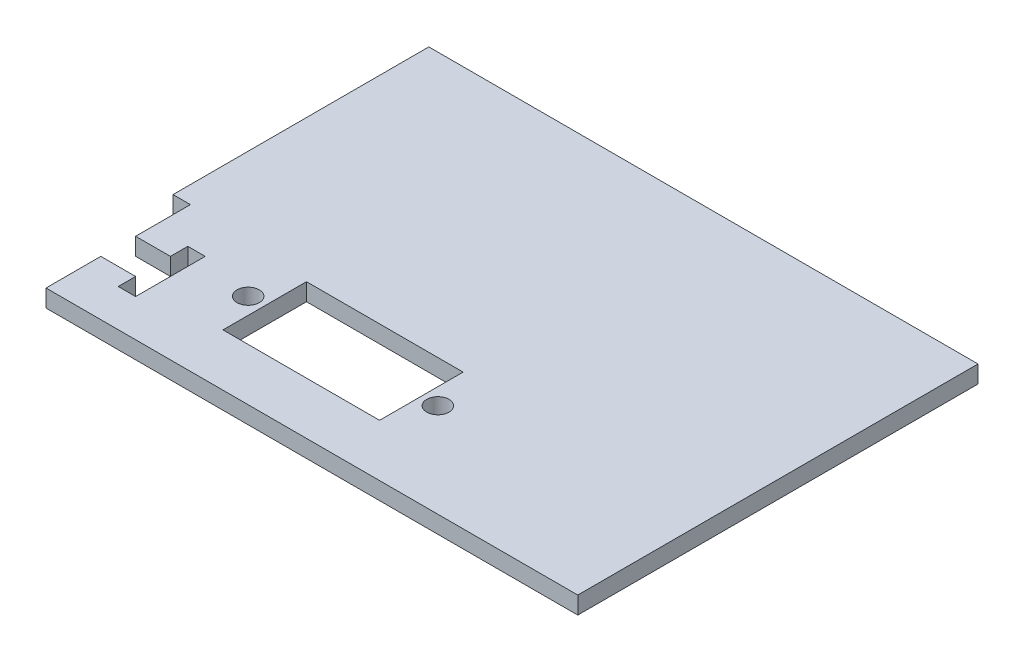
SolidWorks part; units mm, degrees
ref_plane "Front Plane" through (0, 0, 0) normal (0, 0, 1) x (1, 0, 0)
ref_plane "Top Plane" through (0, 0, 0) normal (0, 1, 0) x (1, 0, 0)
ref_plane "Right Plane" through (0, 0, 0) normal (1, 0, 0) x (0, 0, -1)
sketch "Sketch1" plane through (0, 0, 0) normal (0, 1, 0) x (1, 0, 0)
  line L1 (40, -30) -> (-40, -30)
  line L2 (40, -30) -> (40, 30)
  line L3 (40, 30) -> (-40, 30)
  line L4 (-40, -30) -> (-40, 30)
  line L5 (40, -30) -> (-40, 30) construction
  line L6 (40, 30) -> (-40, -30) construction
  point P0 (0, 0)
  dimension "D1" = 80
  dimension "D2" = 60
extrude "Boss-Extrude1" add sketch "Sketch1" along normal blind 2.5 contours L2 L1 L4 L3
sketch "Sketch2" plane through (0, 0, 0) normal (0, 1, 0) x (1, 0, 0)
  line L0 (0, -30) -> (0, -24)
  line L1 (40, -30) -> (-40, -30) construction
  line L2 (-11, -24) -> (21, -24)
  line L3 (-8.625, -24) -> (0, -24)
  line L4 (-11, -24) -> (-6.25, -24)
  line L5 (21, -24) -> (16.25, -24)
  line L6 (16.25, -30) -> (-6.25, -30)
  line L7 (16.25, -30) -> (16.25, -18)
  line L8 (16.25, -18) -> (-6.25, -18)
  line L9 (-6.25, -30) -> (-6.25, -18)
  line L10 (16.25, -30) -> (-6.25, -18) construction
  line L11 (16.25, -18) -> (-6.25, -30) construction
  line L12 (-10.225, -24) -> (0, -24)
  line L13 (-8.625, -24) -> (0, -24)
  circle A2 centre (0, -24) radius 2.5
  circle A3 centre (-8.625, -24) radius 1.6
  circle A4 centre (18.625, -24) radius 1.6
  point P5 (0, -30)
  point P15 (5, -24)
  dimension "D5" = 3.2
  dimension "D7" = 3.2
  dimension "D8" = 5
  dimension "D1" = 6
  dimension "D2" = 11
  dimension "D3" = 32
  dimension "D4" = 4.75
  dimension "D6" = 4.75
  dimension "D9" = 12
  dimension "D10" = 22.5
extrude "Cut-Extrude4" cut sketch "Sketch2" against normal through all and the other way through all contours A2 L2 L7 L8 L9 | A2 L0 L6 L7 L2 | L0 A2 L2 | L2 A2 | L2 A2 L0 | A2 L2 L9 L6 L0 | A3 | A4
sketch "Sketch3" plane through (0, 2.5, 0) normal (0, 1, 0) x (1, 0, 0)
  line L0 (-10.225, -24) -> (0.275, -24)
  line L3 (-40, -30) -> (-37.5, -30)
  line L4 (-40, -30) -> (-40, -9.5)
  line L5 (-40, -9.5) -> (-37.5, -9.5)
  line L6 (-37.5, -30) -> (-37.5, -9.5)
  circle A0 centre (-8.625, -24) radius 1.6 construction
  line M13 (-40, 30) -> (-40, -30)
  line M14 (-40, -30) -> (-6.25, -30)
  dimension "D1" = 10.5
  dimension "D2" = 2.5
  dimension "D3" = 20.5
extrude "Boss-Extrude2" add sketch "Sketch3" along normal blind 66.5 contours L6 L5 M14 M13
sketch "Sketch4" plane through (0, 2.5, 0) normal (0, 1, 0) x (1, 0, 0)
  line L1 (40, -30) -> (-40, -30)
  line L2 (40, -30) -> (40, -35.5)
  line L3 (40, -35.5) -> (-40, -35.5)
  line L4 (-40, -30) -> (-40, -35.5)
  dimension "D1" = 5.5
extrude "Boss-Extrude3" add sketch "Sketch4" against normal up to surface (2.5 mm away) up to face at (18.625, 0, 22.4)
sketch "Sketch5" plane through (0, 2.5, 0) normal (0, 1, 0) x (1, 0, 0)
  line L1 (-37.5, -30) -> (-40, -30)
  line L2 (-37.5, -30) -> (-37.5, -35.5)
  line L3 (-37.5, -35.5) -> (-40, -35.5)
  line L4 (-40, -30) -> (-40, -35.5)
extrude "Boss-Extrude4" add sketch "Sketch5" along normal up to surface (66.5 mm away) up to face at (-38.75, 69, 19.75)
sketch "Sketch6" plane through (0, 69, 0) normal (0, 1, 0) x (1, 0, 0)
  line L0 (-37.5, -35.5) -> (-37.5, -9.5) construction
  line L1 (-40, -9.5) -> (-37.5, -9.5)
  line L2 (-40, -9.5) -> (-40, -15)
  line L3 (-40, -15) -> (-37.5, -15)
  line L4 (-37.5, -9.5) -> (-37.5, -15)
  dimension "D1" = 5.5
extrude "Cut-Extrude5" cut sketch "Sketch6" against normal up to surface (66.5 mm away) up to face at (5, 2.5, 24)
sketch "Sketch7" plane through (0, 2.5, 0) normal (0, 1, 0) x (1, 0, 0)
  line L0 (-10.225, -24) -> (0.275, -24)
  line L1 (15.525, -24) -> (-14.975, -24)
  line L2 (15.525, -24) -> (18.625, -24)
  line L3 (-14.975, -24) -> (-24.175, -24)
  circle A0 centre (-8.625, -24) radius 1.6 construction
  point P8 (0.275, -24)
  dimension "D4" = 9.2
  dimension "D1" = 10.5
  dimension "D2" = 30.5
  dimension "D3" = 3.1
sketch "Sketch9" plane through (0, 2.5, 0) normal (0, 1, 0) x (1, 0, 0)
  line L0 (-10.225, -24) -> (-37.5, -24)
  line L1 (-37.5, -35.5) -> (-37.5, -15) construction
  line L2 (-37.5, -24) -> (-37.5, -35.5)
  line L3 (-37.5, -24) -> (-37.5, -12.5)
  line L4 (-37.5, -12.5) -> (-40, -12.5)
  line L5 (-40, -15) -> (-40, 30) construction
  line L6 (-40, -12.5) -> (-40, -15)
  line L7 (-40, -15) -> (-37.5, -15) construction
  line L8 (-40, -15) -> (-37.5, -15)
  line L9 (-37.5, -15) -> (-37.5, -12.5)
  dimension "D1" = 11.5
extrude "Boss-Extrude5" add sketch "Sketch9" along normal up to surface (66.5 mm away) contours L4 L6 L8 L9 up to face at (-38.75, 69, 25.25)
sketch "Sketch11" plane through (-37.5, 0, 0) normal (1, 0, 0) x (0, 0, -1)
  line L0 (-24, 69) -> (-24, 54)
  line L1 (-35.5, 69) -> (-12.5, 69) construction
  circle A0 centre (-24, 54) radius 4.75
  dimension "D2" = 9.5
  dimension "D1" = 15
extrude "Cut-Extrude6" cut sketch "Sketch11" against normal up to surface (2.5 mm away) contours A0 up to face at (-40, 23.8333, 6)
sketch "Sketch13" plane through (-40, 0, 0) normal (-1, 0, 0) x (0, 0, 1)
  line L0 (24, 54) -> (32, 54)
  line L1 (32, 36.5) -> (32, 71.5)
  point P7 (32, 54)
  dimension "D1" = 8
  dimension "D2" = 35
sketch "Sketch15" plane through (0, 69, 0) normal (0, 1, 0) x (1, 0, 0)
  line L1 (-40, -12.5) -> (-37.5, -12.5)
  line L2 (-40, -12.5) -> (-40, -35.5)
  line L3 (-40, -35.5) -> (-37.5, -35.5)
  line L4 (-37.5, -12.5) -> (-37.5, -35.5)
extrude "Boss-Extrude6" add sketch "Sketch15" along normal blind 8
sketch "Sketch17" plane through (0, 0, 35.5) normal (0, 0, 1) x (1, 0, 0)
  line L1 (-40, 77) -> (-37.5, 77)
  line L2 (-40, 77) -> (-40, 2.5)
  line L3 (-40, 2.5) -> (-37.5, 2.5)
  line L4 (-37.5, 77) -> (-37.5, 2.5)
extrude "Boss-Extrude7" add sketch "Sketch17" along normal blind 2
sketch "Sketch18" plane through (-40, 0, 0) normal (-1, 0, 0) x (0, 0, 1)
  circle A0 centre (32, 36.5) radius 1.6
  circle A1 centre (32, 71.5) radius 1.6
  dimension "D1" = 3.2
  dimension "D2" = 3.2
extrude "Cut-Extrude7" cut sketch "Sketch18" against normal up to surface (2.5 mm away) up to face at (-37.5, 54, 19.25)
sketch "Sketch21" plane through (0, 0, 35.5) normal (0, 0, 1) x (1, 0, 0)
  line L1 (-40, 2.5) -> (40, 2.5)
  line L2 (-40, 2.5) -> (-40, 0)
  line L3 (-40, 0) -> (40, 0)
  line L4 (40, 2.5) -> (40, 0)
extrude "Boss-Extrude8" add sketch "Sketch21" along normal up to surface (2 mm away) up to face at (-38.75, 39.75, 37.5)
sketch "Sketch22" plane through (-37.5, 0, 0) normal (1, 0, 0) x (0, 0, -1)
  line L0 (-37.5, 2.5) -> (-12.5, 2.5) construction
  line L1 (-12.5, 77) -> (-16.75, 77)
  line L2 (-12.5, 77) -> (-12.5, 2.5)
  line L3 (-12.5, 2.5) -> (-16.75, 2.5)
  line L4 (-16.75, 77) -> (-16.75, 2.5)
  dimension "D1" = 4.25
extrude "Cut-Extrude8" cut sketch "Sketch22" against normal up to surface (2.5 mm away) up to face at (-40, 36.5, 33.6)
fillet "Fillet1" radius 5 2 edges at (-38.75, 77, 37.5) (-38.75, 77, 16.75)
sketch "Sketch23" plane through (0, 2.5, 0) normal (0, 1, 0) x (1, 0, 0)
  line L0 (20.225, -24) -> (55.225, -24)
  line L1 (40, 30) -> (40, -37.5)
  line L6 (40, -37.5) -> (55.225, -37.5)
  line L7 (55.225, -37.5) -> (55.225, 30)
  line L8 (55.225, 30) -> (40, 30)
  circle A0 centre (18.625, -24) radius 1.6 construction
  dimension "D1" = 35
extrude "Boss-Extrude10" add sketch "Sketch23" against normal up to surface (2.5 mm away) contours L8 L1 L6 L7 up to face at (0, 0, 3.75)
sketch "Sketch24" plane through (0, 2.5, 0) normal (0, 1, 0) x (1, 0, 0)
  line L0 (55.225, -37.5) -> (55.225, 30) construction
  line L1 (-40, 30) -> (55.225, 30)
  line L2 (-40, 30) -> (-40, 20)
  line L3 (-40, 20) -> (55.225, 20)
  line L4 (55.225, 30) -> (55.225, 20)
  dimension "D1" = 10
extrude "Cut-Extrude9" cut sketch "Sketch24" against normal through all
sketch "Sketch26" plane through (0, 2.5, 0) normal (0, 1, 0) x (1, 0, 0)
  line L0 (-24.175, -37.5) -> (-24.175, -16.75)
  line L1 (55.225, -37.5) -> (-37.5, -37.5) construction
  line L2 (-24.175, -16.75) -> (-26.675, -16.75)
  line L3 (-26.675, -16.75) -> (-26.675, -37.5)
  line L4 (-26.675, -37.5) -> (-24.175, -37.5)
extrude "Boss-Extrude11" add sketch "Sketch26" along normal up to surface (74.5 mm away) up to face at (-38.75, 77, 27.125)
sketch "Sketch27" plane through (-24.175, 0, 0) normal (1, 0, 0) x (0, 0, -1)
  line L0 (-24, 2.5) -> (-24, 36.275)
  line L2 (-24, 36.275) -> (-32, 36.275)
  line L4 (-32, 18.775) -> (-32, 53.775)
  circle A0 centre (-24, 36.275) radius 4.75
  circle A1 centre (-32, 53.775) radius 1.6
  circle A2 centre (-32, 18.775) radius 1.6
  point P4 (-32, 36.275)
  dimension "D2" = 9.5
  dimension "D5" = 3.2
  dimension "D6" = 3.2
  dimension "D1" = 33.775
  dimension "D3" = 8
  dimension "D4" = 35
extrude "Cut-Extrude10" cut sketch "Sketch27" against normal up to surface (2.5 mm away) contours L0 A0 L2 | L2 A0 L0 | A2 | A1 up to face at (-26.675, 39.75, 27.125)
sketch "Sketch28" plane through (0, 77, 0) normal (0, 1, 0) x (1, 0, 0)
  line L1 (-40, -16.75) -> (-37.5, -16.75)
  line L2 (-40, -16.75) -> (-40, -37.5)
  line L3 (-40, -37.5) -> (-37.5, -37.5)
  line L4 (-37.5, -16.75) -> (-37.5, -37.5)
extrude "Cut-Extrude11" cut sketch "Sketch28" against normal up to surface (74.5 mm away) up to face at (5, 2.5, 24)
sketch "Sketch29" plane through (-24.175, 0, 0) normal (1, 0, 0) x (0, 0, -1)
  line L0 (-32, 55.375) -> (-32, 57.375)
  line L1 (-32, 36.5) -> (-32, 71.5) construction
  line L2 (-16.75, 77) -> (-16.75, 2.5) construction
  line L3 (-37.5, 77) -> (-16.75, 77)
  line L4 (-37.5, 77) -> (-37.5, 57.375)
  line L5 (-37.5, 57.375) -> (-16.75, 57.375)
  line L6 (-16.75, 77) -> (-16.75, 57.375)
  circle A0 centre (-32, 53.775) radius 1.6 construction
  dimension "D1" = 2
extrude "Cut-Extrude12" cut sketch "Sketch29" against normal up to surface (2.5 mm away) contours L4 L3 L6 L5 up to face at (-26.675, 36.275, 19.25)
fillet "Fillet2" radius 6 2 edges at (-25.425, 57.375, 16.75) (-25.425, 57.375, 37.5)
sketch "Sketch31" plane through (0, 2.5, 0) normal (0, 1, 0) x (1, 0, 0)
  line L1 (-40, 20) -> (-26.675, 20)
  line L2 (-40, 20) -> (-40, -37.5)
  line L3 (-40, -37.5) -> (-26.675, -37.5)
  line L4 (-26.675, 20) -> (-26.675, -37.5)
extrude "Cut-Extrude13" cut sketch "Sketch31" against normal up to surface (2.5 mm away) up to face at (7.6125, 0, 8.75)
sketch "Sketch33" plane through (0, 2.5, 0) normal (0, 1, 0) x (1, 0, 0)
  line L0 (55.225, -37.5) -> (-24.175, -37.5) construction
  line L1 (55.225, 20) -> (52.225, 20)
  line L2 (55.225, 20) -> (55.225, -37.5)
  line L3 (55.225, -37.5) -> (52.225, -37.5)
  line L4 (52.225, 20) -> (52.225, -37.5)
  dimension "D1" = 3
extrude "Cut-Extrude14" cut sketch "Sketch33" against normal up to surface (2.5 mm away) up to face at (14.275, 0, 8.75)
sketch "Sketch34" plane through (0, 2.5, 0) normal (0, 1, 0) x (1, 0, 0)
  line L0 (-24.175, -27.125) -> (-24.175, -24.625)
  line L1 (-24.175, -37.5) -> (-24.175, -16.75) construction
  line L2 (-24.175, -27.125) -> (-24.175, -29.625)
  line L3 (-16.675, -32.125) -> (-16.675, -22.125)
  line L4 (-19.175, -24.625) -> (-19.175, -22.125)
  line L5 (-24.175, -29.625) -> (-19.175, -29.625)
  line L6 (-24.175, -29.625) -> (-24.175, -24.625)
  line L7 (-24.175, -24.625) -> (-19.175, -24.625)
  line L8 (-19.175, -29.625) -> (-19.175, -24.625)
  line L9 (-19.175, -29.625) -> (-19.175, -32.125)
  line L10 (-19.175, -32.125) -> (-16.675, -32.125)
  line L11 (-16.675, -22.125) -> (-19.175, -22.125)
  dimension "D1" = 2.5
  dimension "D2" = 2.5
  dimension "D3" = 5
  dimension "D4" = 2.5
  dimension "D5" = 2.5
  dimension "D6" = 2.5
extrude "Cut-Extrude15" cut sketch "Sketch34" against normal up to surface (2.5 mm away)
sketch "Sketch35" plane through (0, 57.375, 0) normal (0, 1, 0) x (1, 0, 0)
  line L1 (-24.175, -16.75) -> (-26.675, -16.75)
  line L2 (-24.175, -16.75) -> (-24.175, -37.5)
  line L3 (-24.175, -37.5) -> (-26.675, -37.5)
  line L4 (-26.675, -16.75) -> (-26.675, -37.5)
extrude "Cut-Extrude16" cut sketch "Sketch35" against normal up to surface (57.375 mm away) up to face at (-19.8, 0, 27.125)
